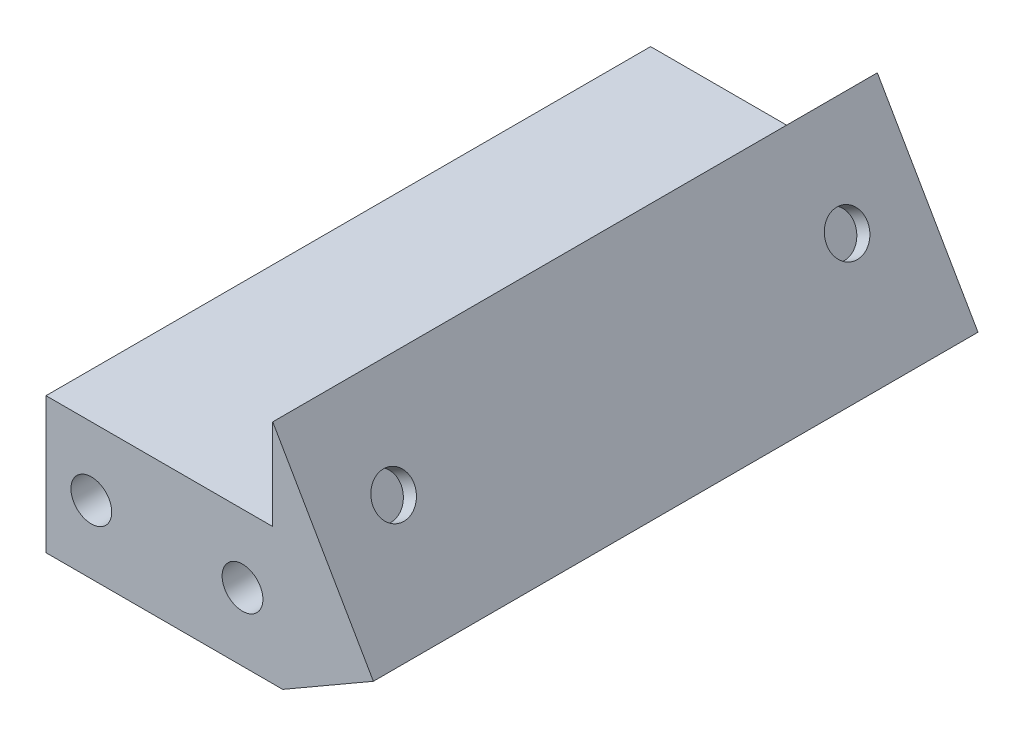
SolidWorks part; units mm, degrees
ref_plane "Front" through (0, 0, 0) normal (0, 0, 1) x (1, 0, 0)
ref_plane "Top" through (0, 0, 0) normal (0, 1, 0) x (1, 0, 0)
ref_plane "Right" through (0, 0, 0) normal (1, 0, 0) x (0, 0, -1)
sketch "草图1" plane through (0, 0, 0) normal (0, 0, 1) x (1, 0, 0)
  line L0 (0, 0) -> (15, 0)
  line L1 (15, 0) -> (15, 6)
  line L2 (21.6603, -5.5359) -> (15.6603, -9)
  line L3 (0, 0) -> (0, -9)
  line L4 (0, -9) -> (15.6603, -9)
  line L6 (15, 6) -> (21.6603, -5.5359)
extrude "凸台-拉伸1" add sketch "草图1" along normal blind 40
sketch "草图2" plane through (13.8481, 7.9952, 0) normal (0.866, 0.5, 0) x (0, 0, -1)
  circle A0 centre (-5, -8.3038) radius 1.35
extrude "切除-拉伸1" cut sketch "草图2" against normal blind 1
ref_plane "基准面1" through (0, 0, 20) normal (0, 0, 1) x (1, 0, 0)
mirror "镜向1" about plane through (0, 0, 20) normal (0, 0, 1) of "切除-拉伸1"
sketch "草图3" plane through (0, 0, 40) normal (0, 0, 1) x (1, 0, 0)
  circle A0 centre (3, -4.5) radius 1.35
  circle A1 centre (13, -4.5) radius 1.35
extrude "切除-拉伸2" cut sketch "草图3" against normal blind 40
